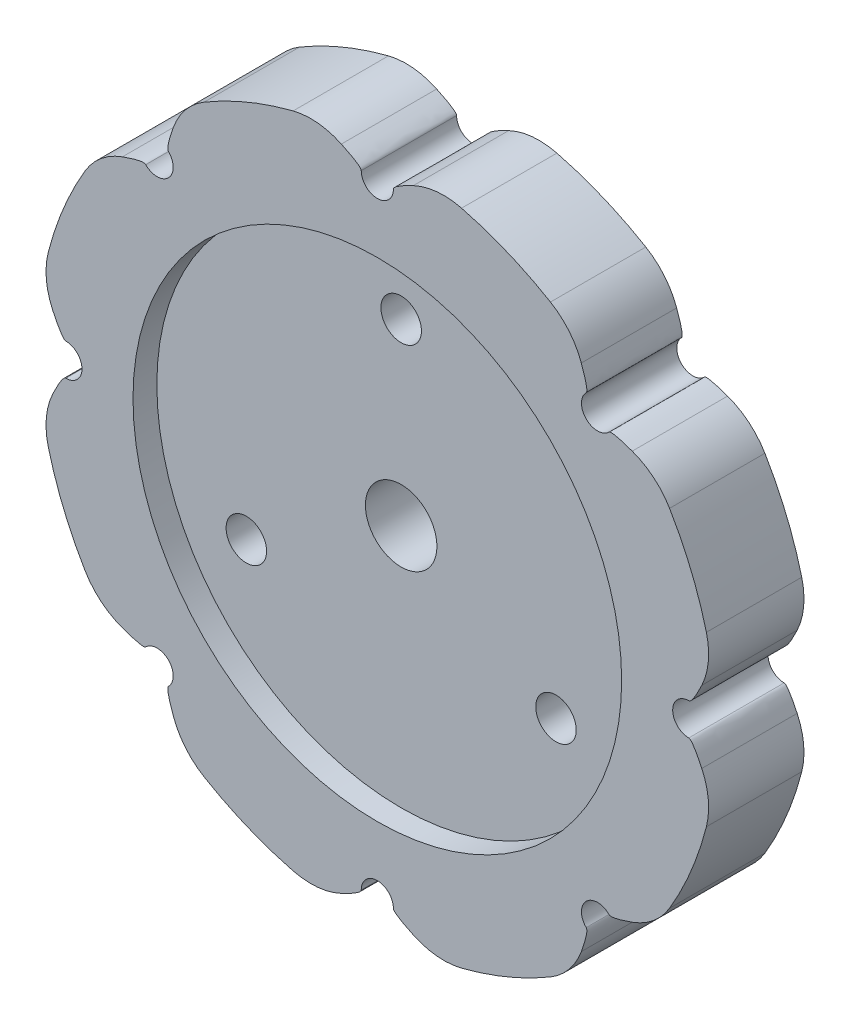
SolidWorks part; units mm, degrees
ref_plane "Plan de face" through (0, 0, 0) normal (0, 0, 1) x (1, 0, 0)
ref_plane "Plan de dessus" through (0, 0, 0) normal (0, 1, 0) x (1, 0, 0)
ref_plane "Plan de droite" through (0, 0, 0) normal (1, 0, 0) x (0, 0, -1)
sketch "Esquisse1" plane through (0, 0, 0) normal (0, 0, 1) x (1, 0, 0)
  circle A0 centre (0, 0) radius 28.5
  dimension "D1" = 57
extrude "Boss.-Extru.1" add sketch "Esquisse1" along normal mid plane 8
ref_axis "Axe1" through (0, 0, 5.7978) along (0, 0, -1)
sketch "Esquisse2" plane through (0, 0, 0) normal (0, 0, 1) x (1, 0, 0)
  line L0 (0, 0) -> (0, 42.1559) construction
  line L1 (1.35, 26.1313) -> (1.35, 26.5808) construction
  line L2 (1.35, 26.5808) -> (4.949, 28.067) construction
  line L3 (0, 0) -> (-4.949, 28.067) construction
  line L4 (-1.35, 26.1313) -> (-1.35, 26.5808) construction
  line L5 (-1.35, 26.5808) -> (-4.949, 28.067) construction
  line L6 (0, 0) -> (4.949, 28.067) construction
  line L7 (0, 26.1313) -> (-18.4776, 18.4776) construction
  line L8 (-18.4776, 18.4776) -> (-26.1313, 0) construction
  line L9 (-26.1313, 0) -> (-18.4776, -18.4776) construction
  line L10 (-18.4776, -18.4776) -> (0, -26.1313) construction
  line L11 (0, -26.1313) -> (18.4776, -18.4776) construction
  line L12 (18.4776, -18.4776) -> (26.1313, 0) construction
  line L13 (26.1313, 0) -> (18.4776, 18.4776) construction
  line L14 (18.4776, 18.4776) -> (0, 26.1313) construction
  circle A0 centre (0, 0) radius 28.5 construction
  circle A1 centre (0, 0) radius 26.1313 construction
  arc A2 (-1.35, 26.1313) -> (1.35, 26.1313) centre (0, 26.1313) ccw
  arc A3 (-4.949, 28.067) -> (4.949, 28.067) centre (0, 0) cw
  arc A4 (0, 26.1313) -> (18.4776, 18.4776) centre (0, 0) cw construction
  spline S0 degree 2 poles (1.35, 26.1313) (1.35, 26.5808) (4.949, 28.067) knots 0 0 0 1 1 1
  spline S1 degree 2 poles (-1.35, 26.1313) (-1.35, 26.5808) (-4.949, 28.067) knots 0 0 0 1 1 1
  dimension "D2" = 20
  dimension "D3" = 2.7
  dimension "D4" = 20
extrude "Enlèv. mat.-Extru.1" cut sketch "Esquisse2" against normal through all both and the other way through all
fillet "Congé1" radius 6 2 edges at (4.949, 28.067, 0) (-4.949, 28.067, 0)
pattern_circular "Répétition circulaire1" count 8 over 360 about axis through (0, 0, 5.7978) along (0, 0, -1) of "Enlèv. mat.-Extru.1", "Congé1"
hole_wizard "Diamètre du perçage Ø6.0 (6)1" positions "Esquisse5" profile "Esquisse4" hole size "Ø6.0" standard "Ansi Metric" end condition through all
sketch "Esquisse5" plane through (0, 0, 4) normal (0, 0, 1) x (1, 0, 0)
  point P0 (0, 0)
sketch "Esquisse4" plane through (0, 0, 4) normal (1, 0, 0) x (0, -1, 0)
  line L0 (0, 0) -> (0, 8)
  line L1 (0, 8) -> (3, 8)
  line L2 (3, 8) -> (3, 0)
  line L5 (3, 0) -> (0, 0)
  line L11 (0, -6.35) -> (0, 107.95) construction
  dimension "Diamètre du perçage jusqu'au prochain" = 6
  dimension "Profondeur du perçage jusqu'au prochain" = 8
sketch "Esquisse6" plane through (0, 0, 4) normal (0, 0, 1) x (1, 0, 0)
  line L0 (0, 26.0973) -> (0, 0.066) construction
  circle A0 centre (0, 26.0313) radius 1.25 construction
  arc A1 (-1.35, 26.1313) -> (1.35, 26.1313) centre (0, 26.1313) ccw construction
  dimension "D1" = 2.5
  dimension "rayon_pigonon" = 26.0313
hole_wizard "Dégagement M31" positions "Esquisse8" profile "Esquisse7" hole size "M3" standard "Ansi Metric" end condition through all
sketch "Esquisse8" plane through (0, 0, 4) normal (0, 0, 1) x (1, 0, 0)
  line L0 (0, 15) -> (-12.9904, -7.5)
  line L1 (-12.9904, -7.5) -> (12.9904, -7.5)
  line L2 (12.9904, -7.5) -> (0, 15)
  circle A0 centre (0, 0) radius 15
  point P0 (0, 15)
  point P2 (-12.9904, -7.5)
  point P4 (12.9904, -7.5)
  dimension "D1" = 30
sketch "Esquisse7" plane through (0, 15, 4) normal (1, 0, 0) x (0, -1, 0)
  line L0 (0, 0) -> (0, 8)
  line L1 (0, 8) -> (1.7, 8)
  line L2 (1.7, 8) -> (1.7, 0)
  line L5 (1.7, 0) -> (0, 0)
  line L11 (0, -6.35) -> (0, 107.95) construction
  dimension "Diamètre du perçage jusqu'au prochain" = 3.4
  dimension "Profondeur du perçage jusqu'au prochain" = 8
sketch "Esquisse9" plane through (0, 0, 4) normal (0, 0, 1) x (1, 0, 0)
  circle A0 centre (0, 0) radius 20.5
  dimension "D1" = 41
extrude "Enlèv. mat.-Extru.2" cut sketch "Esquisse9" against normal blind 2
equation "\"rayon_pignon\" = 26.0313"
